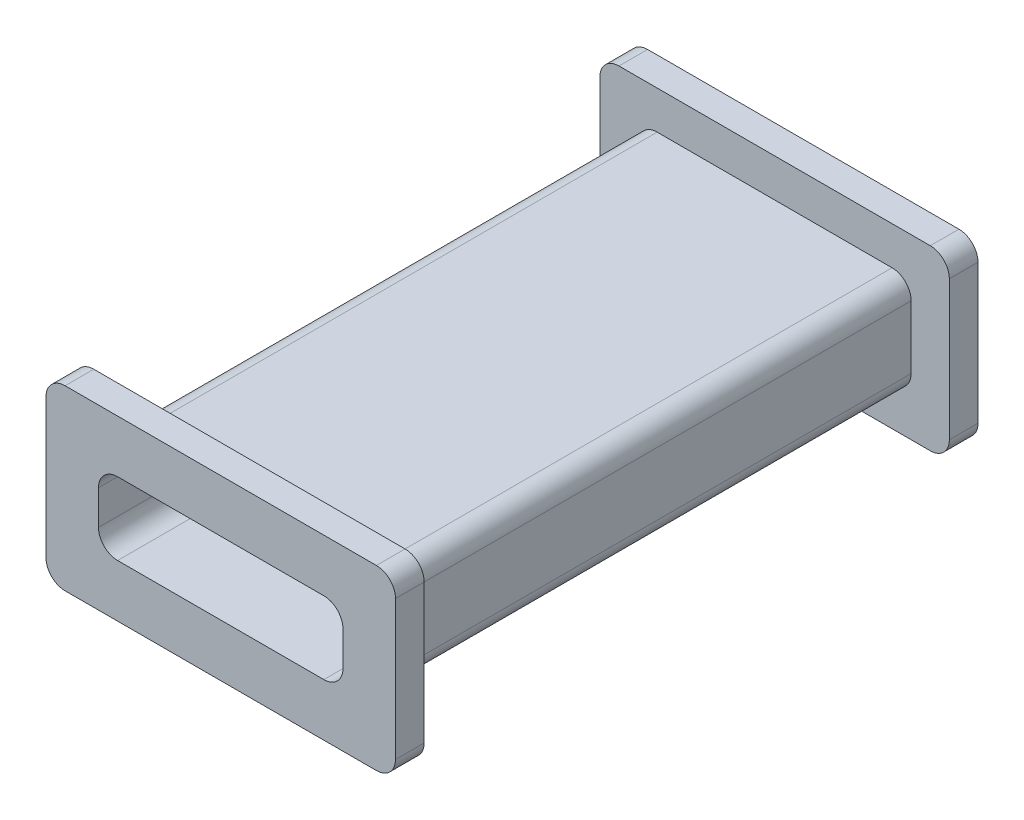
SolidWorks part; units mm, degrees
material "7079 Alloy"
ref_plane "Front Plane" through (0, 0, 0) normal (0, 0, 1) x (1, 0, 0)
ref_plane "Top Plane" through (0, 0, 0) normal (0, 1, 0) x (1, 0, 0)
ref_plane "Right Plane" through (0, 0, 0) normal (1, 0, 0) x (0, 0, -1)
sketch "Sketch1" plane through (0, 0, 0) normal (0, 0, 1) x (1, 0, 0)
  line L1 (-12.8, -3.8) -> (12.8, -3.8)
  line L2 (-12.8, -3.8) -> (-12.8, 3.8)
  line L3 (-12.8, 3.8) -> (12.8, 3.8)
  line L4 (12.8, -3.8) -> (12.8, 3.8)
  line L5 (-12.8, -3.8) -> (12.8, 3.8) construction
  line L6 (-12.8, 3.8) -> (12.8, -3.8) construction
  line L7 (-14.3, -5.3) -> (14.3, -5.3)
  line L8 (-14.3, -5.3) -> (-14.3, 5.3)
  line L9 (-14.3, 5.3) -> (14.3, 5.3)
  line L10 (14.3, -5.3) -> (14.3, 5.3)
  line L11 (-14.3, -5.3) -> (14.3, 5.3) construction
  line L12 (-14.3, 5.3) -> (14.3, -5.3) construction
  point P0 (0, 0)
  point P6 (0, 0)
  dimension "D1" = 1.5
  dimension "D2" = 1.5
  dimension "D3" = 10.6
  dimension "D4" = 25.6
extrude "Boss-Extrude1" add sketch "Sketch1" along normal blind 55
sketch "Sketch2" plane through (0, 0, 55) normal (0, 0, 1) x (1, 0, 0)
  line L0 (14.3, 5.3) -> (-14.3, 5.3) construction
  line L1 (-18.3, -9.3) -> (18.3, -9.3)
  line L2 (-18.3, -9.3) -> (-18.3, 9.3)
  line L3 (-18.3, 9.3) -> (18.3, 9.3)
  line L4 (18.3, -9.3) -> (18.3, 9.3)
  line L5 (-18.3, -9.3) -> (18.3, 9.3) construction
  line L6 (-18.3, 9.3) -> (18.3, -9.3) construction
  line L7 (-14.3, 5.3) -> (-14.3, -5.3) construction
  line L9 (-12.8, -3.8) -> (12.8, -3.8)
  line L10 (-12.8, -3.8) -> (-12.8, 3.8)
  line L11 (-12.8, 3.8) -> (12.8, 3.8)
  line L12 (12.8, -3.8) -> (12.8, 3.8)
  line L13 (-12.8, -3.8) -> (12.8, 3.8) construction
  line L14 (-12.8, 3.8) -> (12.8, -3.8) construction
  point P0 (0, 0)
  point P10 (0, 0)
  dimension "D1" = 4
  dimension "D2" = 4
extrude "Boss-Extrude3" add sketch "Sketch2" along normal blind 3
fillet "Fillet2" radius 2 4 edges at (-18.3, -9.3, 56.5) (18.3, -9.3, 56.5) (-18.3, 9.3, 56.5) (18.3, 9.3, 56.5)
sketch "Sketch3" plane through (0, 0, 58) normal (0, 0, 1) x (1, 0, 0)
  line L0 (-12.8, 3.8) -> (-12.8, -3.8) construction
  line L1 (-15.8, -6.3) -> (15.8, -6.3)
  line L2 (-15.8, -6.3) -> (-15.8, 6.3)
  line L3 (-15.8, 6.3) -> (15.8, 6.3)
  line L4 (15.8, -6.3) -> (15.8, 6.3)
  line L5 (-15.8, -6.3) -> (15.8, 6.3) construction
  line L6 (-15.8, 6.3) -> (15.8, -6.3) construction
  line L7 (-12.8, -3.8) -> (12.8, -3.8) construction
  line L8 (12.8, -3.8) -> (12.8, 3.8) construction
  line L9 (12.8, 3.8) -> (-12.8, 3.8) construction
  line L10 (-12.8, 3.8) -> (-12.8, -3.8)
  line L11 (-12.8, -3.8) -> (12.8, -3.8)
  line L12 (12.8, -3.8) -> (12.8, 3.8)
  line L13 (12.8, 3.8) -> (-12.8, 3.8)
  point P0 (0, 0)
  dimension "D1" = 2.5
  dimension "D2" = 3
ref_plane "Plane1" through (0, 0, 27.5) normal (0, 0, -1) x (-1, 0, 0)
fillet "Fillet1" radius 2 4 edges at (-14.3, -5.3, 27.5) (-14.3, 5.3, 27.5) (14.3, -5.3, 27.5) (14.3, 5.3, 27.5)
mirror "Mirror2" about plane through (0, 0, 27.5) normal (0, 0, -1) of "Fillet2", "Boss-Extrude3"
fillet "Fillet3" radius 2 4 edges at (12.8, -3.8, 27.5) (-12.8, -3.8, 27.5) (-12.8, 3.8, 27.5) (12.8, 3.8, 27.5)
sketch "Sketch4" plane through (0, 0, -3) normal (0, 0, -1) x (-1, 0, 0)
  line L0 (-16.3, 9.3) -> (16.3, 9.3) construction
  point P4 (0, 9.3)
